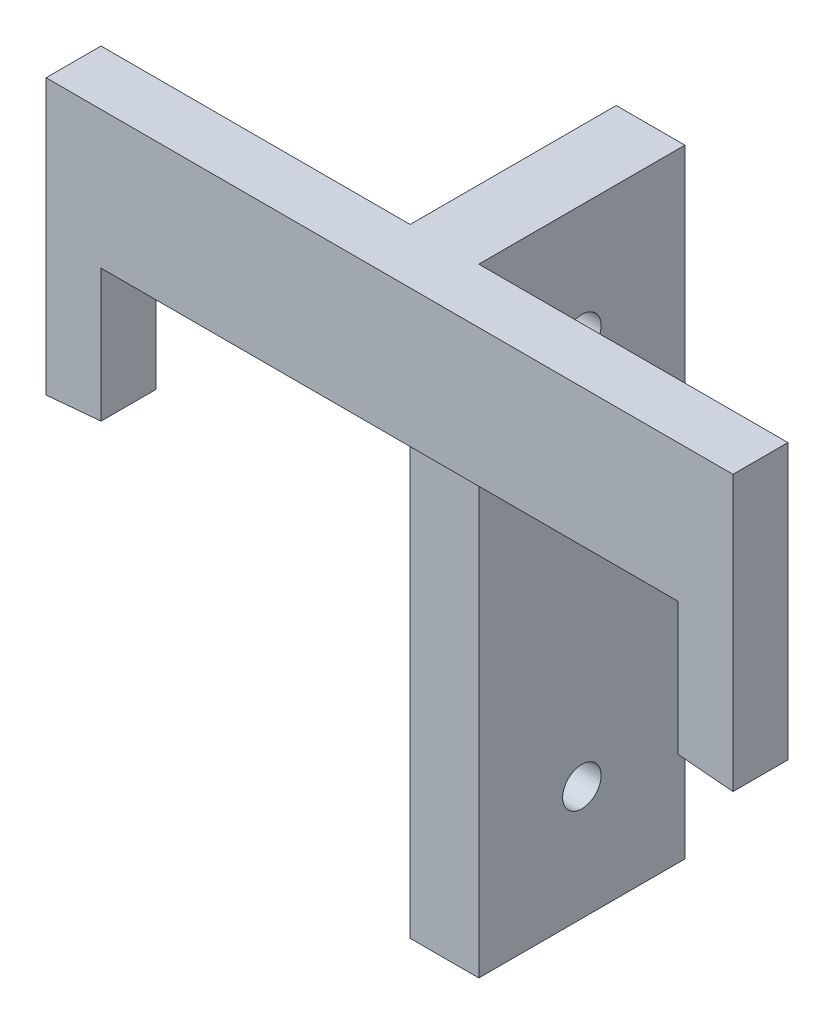
SolidWorks part; units mm, degrees
ref_plane "Front Plane" through (0, 0, 0) normal (0, 0, 1) x (1, 0, 0)
ref_plane "Top Plane" through (0, 0, 0) normal (0, 1, 0) x (1, 0, 0)
ref_plane "Right Plane" through (0, 0, 0) normal (1, 0, 0) x (0, 0, -1)
sketch "Sketch1" plane through (0, 0, 0) normal (0, 0, 1) x (1, 0, 0)
  line L4 (-1.5875, -14.2875) -> (1.5875, -14.2875)
  line L5 (-1.5875, -14.2875) -> (-1.5875, 14.2875)
  line L6 (-1.5875, 14.2875) -> (1.5875, 14.2875)
  line L7 (1.5875, -14.2875) -> (1.5875, 14.2875)
  line L8 (-1.5875, -14.2875) -> (1.5875, 14.2875) construction
  line L9 (-1.5875, 14.2875) -> (1.5875, -14.2875) construction
  point P0 (0, 0)
  dimension "D1" = 28.575
  dimension "D2" = 3.175
extrude "Boss-Extrude1" add sketch "Sketch1" along normal blind 9.525
sketch "Sketch4" plane through (1.5875, 0, 0) normal (1, 0, 0) x (0, 0, -1)
  line L0 (-9.525, 0) -> (0, 0) construction
  line L1 (-9.525, -14.2875) -> (-9.525, 14.2875) construction
  line L2 (-4.7625, 9.0043) -> (-4.7625, -9.0043) construction
  circle A0 centre (-4.7625, -9.0043) radius 0.889
  circle A1 centre (-4.7625, 9.0043) radius 0.889
  point P10 (-4.7625, 0)
  dimension "D2" = 1.778
  dimension "D1" = 9.0043
extrude "Cut-Extrude1" cut sketch "Sketch4" against normal up to next
sketch "Sketch5" plane through (0, 0, 9.525) normal (0, 0, 1) x (1, 0, 0)
  line L0 (-1.5875, 14.2875) -> (1.5875, 14.2875) construction
  line L1 (15.875, 14.2875) -> (-15.875, 14.2875)
  line L2 (15.875, 14.2875) -> (15.875, 7.9375)
  line L3 (15.875, 7.9375) -> (-15.875, 7.9375)
  line L4 (-15.875, 14.2875) -> (-15.875, 7.9375)
  line L5 (15.875, 14.2875) -> (-15.875, 7.9375) construction
  line L6 (15.875, 7.9375) -> (-15.875, 14.2875) construction
  line L7 (15.875, 7.9375) -> (15.875, 1.5875)
  line L8 (15.875, 1.5875) -> (13.335, 1.8097)
  line L9 (13.335, 1.8097) -> (13.335, 7.9375)
  line L10 (13.335, 7.9375) -> (15.875, 7.9375)
  line L11 (0, 14.2875) -> (0, 7.9375) construction
  line L12 (-13.335, 7.9375) -> (-15.875, 7.9375)
  line L13 (-13.335, 1.8097) -> (-13.335, 7.9375)
  line L14 (-15.875, 1.5875) -> (-13.335, 1.8097)
  line L15 (-15.875, 7.9375) -> (-15.875, 1.5875)
  point P0 (0, 11.1125)
  line M5 (1.5875, -14.2875) -> (1.5875, 14.2875)
  line M6 (1.5875, 14.2875) -> (-1.5875, 14.2875)
  line M7 (-1.5875, 14.2875) -> (-1.5875, -14.2875)
  dimension "D1" = 6.35
  dimension "D2" = 31.75
  dimension "D3" = 2.54
  dimension "D4" = 6.35
  dimension "D5" = 85
extrude "Boss-Extrude3" add sketch "Sketch5" along normal blind 2.54 contours L1 L4 L3 M7 | L3 M5 M6 M7 | L3 L2 L1 M5 | L9 L8 L7 L3 | L3 L15 L14 L13
